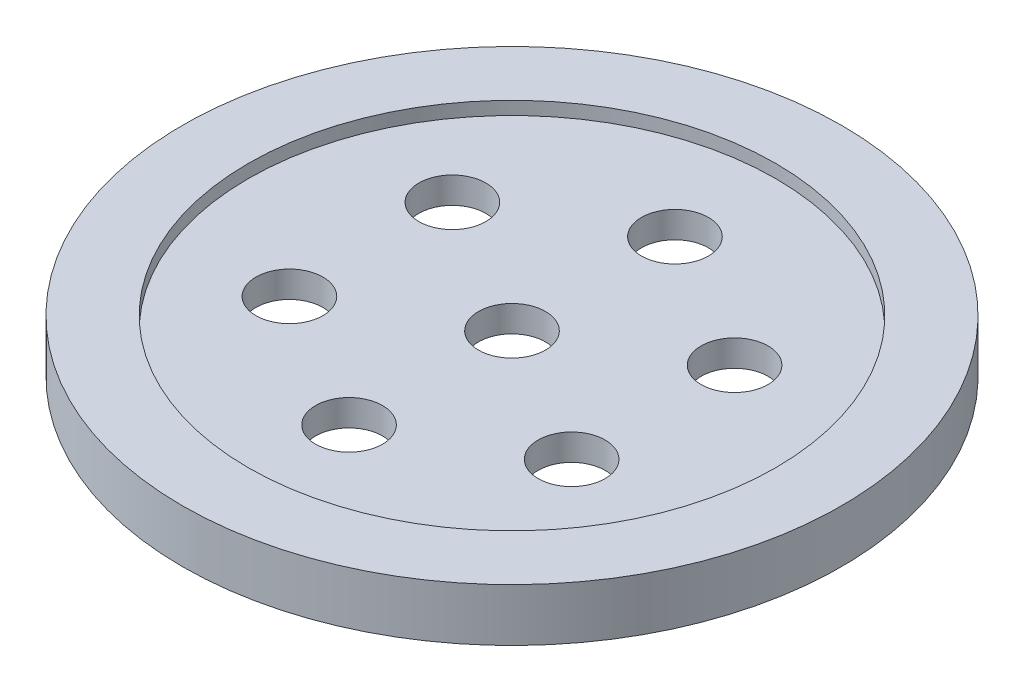
SolidWorks part; units mm, degrees
material "6061-T6 (SS)"
ref_plane "Front Plane" through (0, 0, 0) normal (0, 0, 1) x (1, 0, 0)
ref_plane "Top Plane" through (0, 0, 0) normal (0, 1, 0) x (1, 0, 0)
ref_plane "Right Plane" through (0, 0, 0) normal (1, 0, 0) x (0, 0, -1)
sketch "Sketch1" plane through (0, 0, 0) normal (0, 0, 1) x (1, 0, 0)
  line L0 (0, 113.0498) -> (0, -170.5328) construction
  line L1 (12.7, -4) -> (100, -4)
  line L2 (100, -4) -> (100, 1)
  line L3 (100, 1) -> (125, 1)
  line L4 (125, 1) -> (125, -19)
  line L5 (125, -19) -> (100, -19)
  line L6 (100, -19) -> (100, -14)
  line L7 (100, -14) -> (12.7, -14)
  line L8 (12.7, -4) -> (12.7, -14)
  line L9 (12.7, -9) -> (267.0764, -9) construction
  dimension "D1" = 125
  dimension "D2" = 25.4
  dimension "D3" = 100
  dimension "D4" = 100
  dimension "D5" = 5
  dimension "D6" = 5
  dimension "D7" = 10
  dimension "D8" = 5
revolve "Revolve1" add sketch "Sketch1" angle 360 about L0
sketch "Sketch2" plane through (0, -4, 0) normal (0, 1, 0) x (1, 0, 0)
  circle A0 centre (0, 61.8015) radius 12.7
  circle A1 centre (0, 0) radius 12.7 construction
  circle A2 centre (53.5216, 30.9007) radius 12.7
  circle A3 centre (53.5216, -30.9007) radius 12.7
  circle A4 centre (0, -61.8015) radius 12.7
  circle A5 centre (-53.5216, -30.9007) radius 12.7
  circle A6 centre (-53.5216, 30.9007) radius 12.7
  point P17 (0, 0)
  dimension "D1" = 6
extrude "Cut-Extrude1" cut sketch "Sketch2" against normal blind 10
